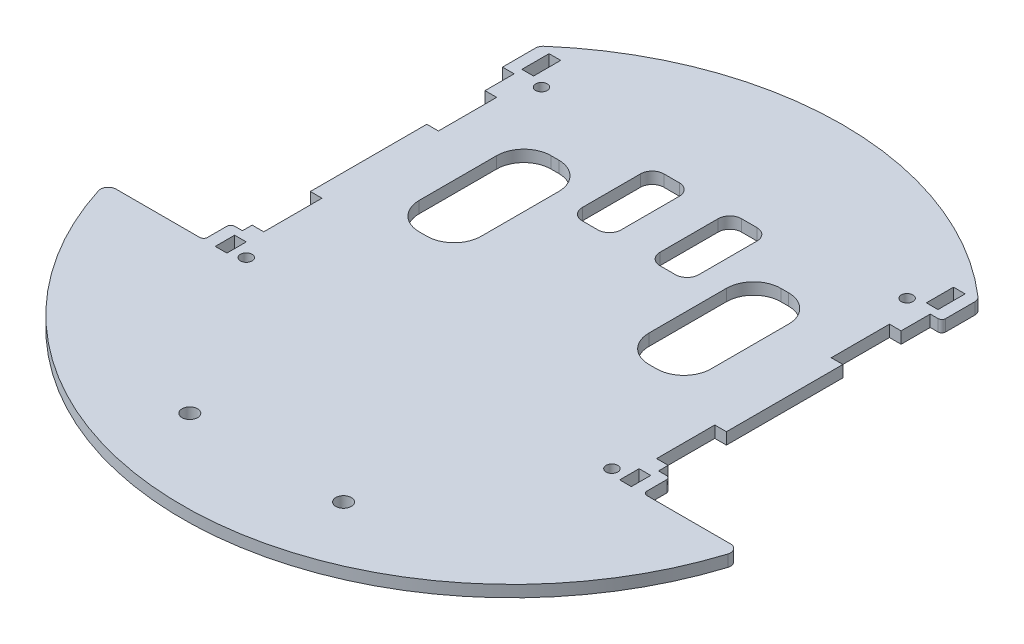
SolidWorks part; units mm, degrees
ref_plane "Front Plane" through (0, 0, 0) normal (0, 0, 1) x (1, 0, 0)
ref_plane "Top Plane" through (0, 0, 0) normal (0, 1, 0) x (1, 0, 0)
ref_plane "Right Plane" through (0, 0, 0) normal (1, 0, 0) x (0, 0, -1)
sketch "Sketch1" plane through (0, 0, 0) normal (0, 1, 0) x (1, 0, 0)
  line L7 (-95.4924, -42.3588) -> (-95.4924, -47.3588)
  line L8 (5.6997, 38.6412) -> (5.6997, 31.6412)
  line L13 (5.6997, -42.3588) -> (8.6997, -42.3588)
  line L38 (-75.4924, 16.1412) -> (-73.4924, 16.1412)
  line L50 (-98.4924, 31.6412) -> (-98.4924, 38.6412)
  line L51 (11.6997, 30.6412) -> (11.6997, 38.128)
  line L52 (10.6997, 29.6412) -> (8.6997, 29.6412)
  line L53 (8.6997, 22.1412) -> (8.6997, 29.6412)
  line L57 (5.6997, 22.1412) -> (8.6997, 22.1412)
  line L58 (5.6997, 22.1412) -> (5.6997, 7.1412)
  line L59 (5.6997, 7.1412) -> (8.6997, 7.1412)
  line L60 (8.6997, -22.8588) -> (8.6997, 7.1412)
  line L61 (8.6997, -22.8588) -> (5.6997, -22.8588)
  line L62 (5.6997, -22.8588) -> (5.6997, -37.8588)
  line L63 (5.6997, -37.8588) -> (8.6997, -37.8588)
  line L64 (8.6997, -40.3588) -> (8.6997, -37.8588)
  line L70 (10.6997, -40.3588) -> (8.6997, -40.3588)
  line L76 (11.6997, -46.3588) -> (11.6997, -41.3588)
  line L77 (34.2584, -47.3588) -> (12.6997, -47.3588)
  line L78 (-124.0511, -47.3588) -> (-102.4924, -47.3588)
  line L79 (-101.4924, -46.3588) -> (-101.4924, -41.3588)
  line L80 (-100.4924, -40.3588) -> (-98.4924, -40.3588)
  line L86 (-98.4924, -40.3588) -> (-98.4924, -37.8588)
  line L87 (-95.4924, -37.8588) -> (-98.4924, -37.8588)
  line L88 (-95.4924, -22.8588) -> (-95.4924, -37.8588)
  line L96 (-98.4924, -22.8588) -> (-95.4924, -22.8588)
  line L97 (-98.4924, -22.8588) -> (-98.4924, 7.1412)
  line L99 (-95.4924, 7.1412) -> (-98.4924, 7.1412)
  line L103 (-95.4924, 22.1412) -> (-95.4924, 7.1412)
  line L104 (-95.4924, 22.1412) -> (-98.4924, 22.1412)
  line L105 (-98.4924, 22.1412) -> (-98.4924, 29.6412)
  line L106 (-98.4924, 29.6412) -> (-101.4924, 29.6412)
  line L107 (-101.4924, 29.6412) -> (-101.4924, 38.128)
  line L108 (-29.8964, 23.6119) -> (-29.8964, 8.6119)
  line L109 (-36.8964, 26.6119) -> (-32.8964, 26.6119)
  line L119 (-39.8964, 8.6119) -> (-39.8964, 23.6119)
  line L124 (-32.8964, 5.6119) -> (-36.8964, 5.6119)
  line L127 (-56.8964, 5.6119) -> (-52.8964, 5.6119)
  line L128 (-49.8964, 8.6119) -> (-49.8964, 23.6119)
  line L130 (-52.8964, 26.6119) -> (-56.8964, 26.6119)
  line L131 (-59.8964, 23.6119) -> (-59.8964, 8.6119)
  line L132 (-7.3003, 9.1412) -> (-7.3003, -10.8295)
  line L133 (-14.3003, 16.1412) -> (-16.3003, 16.1412)
  line L134 (-23.3003, 9.1412) -> (-23.3003, -10.8295)
  line L135 (-16.3003, -17.8295) -> (-14.3003, -17.8295)
  line L136 (-95.4924, -42.3588) -> (-98.4924, -42.3588)
  line L137 (-98.4924, -42.3588) -> (-98.4924, -47.3588)
  line L138 (-98.4924, -47.3588) -> (-95.4924, -47.3588)
  line L139 (5.6997, 31.6412) -> (8.6997, 31.6412)
  line L140 (8.6997, 38.6412) -> (8.6997, 31.6412)
  line L141 (5.6997, 38.6412) -> (8.6997, 38.6412)
  line L142 (5.6997, -42.3588) -> (5.6997, -47.3588)
  line L143 (8.6997, -47.3588) -> (5.6997, -47.3588)
  line L144 (8.6997, -42.3588) -> (8.6997, -47.3588)
  line L145 (-82.4924, 9.1412) -> (-82.4924, -10.8295)
  line L146 (-73.4924, -17.8295) -> (-75.4924, -17.8295)
  line L147 (-66.4924, 9.1412) -> (-66.4924, -10.8295)
  line L148 (-95.4924, 31.6412) -> (-98.4924, 31.6412)
  line L149 (-95.4924, 31.6412) -> (-95.4924, 38.6412)
  line L150 (-95.4924, 38.6412) -> (-98.4924, 38.6412)
  circle A72 centre (2.1997, 30.1875) radius 1.5
  circle A75 centre (2.1997, -45.8588) radius 1.5
  circle A80 centre (-91.9924, -45.8588) radius 1.5
  circle A81 centre (-91.9924, 30.1875) radius 1.5
  circle A84 centre (-24.9424, -87.8588) radius 2
  circle A85 centre (-64.5424, -87.8588) radius 2
  arc A86 (11.6997, 38.128) -> (11.0153, 39.6344) centre (9.6997, 38.128) ccw
  arc A87 (-32.8964, 5.6119) -> (-29.8964, 8.6119) centre (-32.8964, 8.6119) ccw
  arc A88 (-59.8964, 8.6119) -> (-56.8964, 5.6119) centre (-56.8964, 8.6119) ccw
  arc A89 (-14.3003, -17.8295) -> (-7.3003, -10.8295) centre (-14.3003, -10.8295) ccw
  arc A90 (10.6997, 29.6412) -> (11.6997, 30.6412) centre (10.6997, 30.6412) ccw
  arc A103 (11.6997, -41.3588) -> (10.6997, -40.3588) centre (10.6997, -41.3588) ccw
  arc A104 (11.6997, -46.3588) -> (12.6997, -47.3588) centre (12.6997, -46.3588) ccw
  arc A105 (36.1657, -49.9605) -> (34.2584, -47.3588) centre (34.2584, -49.3588) ccw
  arc A106 (-125.9584, -49.9605) -> (36.1657, -49.9605) centre (-44.8964, -24.3881) ccw
  arc A107 (-124.0511, -47.3588) -> (-125.9584, -49.9605) centre (-124.0511, -49.3588) ccw
  arc A108 (-102.4924, -47.3588) -> (-101.4924, -46.3588) centre (-102.4924, -46.3588) ccw
  arc A109 (-100.4924, -40.3588) -> (-101.4924, -41.3588) centre (-100.4924, -41.3588) ccw
  arc A110 (-100.808, 39.6344) -> (-101.4924, 38.128) centre (-99.4924, 38.128) ccw
  arc A111 (11.0153, 39.6344) -> (-100.808, 39.6344) centre (-44.8964, -24.3881) ccw
  arc A112 (-29.8964, 23.6119) -> (-32.8964, 26.6119) centre (-32.8964, 23.6119) ccw
  arc A113 (-36.8964, 26.6119) -> (-39.8964, 23.6119) centre (-36.8964, 23.6119) ccw
  arc A114 (-39.8964, 8.6119) -> (-36.8964, 5.6119) centre (-36.8964, 8.6119) ccw
  arc A115 (-52.8964, 5.6119) -> (-49.8964, 8.6119) centre (-52.8964, 8.6119) ccw
  arc A116 (-49.8964, 23.6119) -> (-52.8964, 26.6119) centre (-52.8964, 23.6119) ccw
  arc A117 (-56.8964, 26.6119) -> (-59.8964, 23.6119) centre (-56.8964, 23.6119) ccw
  arc A118 (-7.3003, 9.1412) -> (-14.3003, 16.1412) centre (-14.3003, 9.1412) ccw
  arc A119 (-16.3003, 16.1412) -> (-23.3003, 9.1412) centre (-16.3003, 9.1412) ccw
  arc A120 (-23.3003, -10.8295) -> (-16.3003, -17.8295) centre (-16.3003, -10.8295) ccw
  arc A121 (-75.4924, 16.1412) -> (-82.4924, 9.1412) centre (-75.4924, 9.1412) ccw
  arc A122 (-82.4924, -10.8295) -> (-75.4924, -17.8295) centre (-75.4924, -10.8295) ccw
  arc A123 (-73.4924, -17.8295) -> (-66.4924, -10.8295) centre (-73.4924, -10.8295) ccw
  arc A124 (-66.4924, 9.1412) -> (-73.4924, 16.1412) centre (-73.4924, 9.1412) ccw
extrude "Boss-Extrude1" add sketch "Sketch1" along normal blind 3
